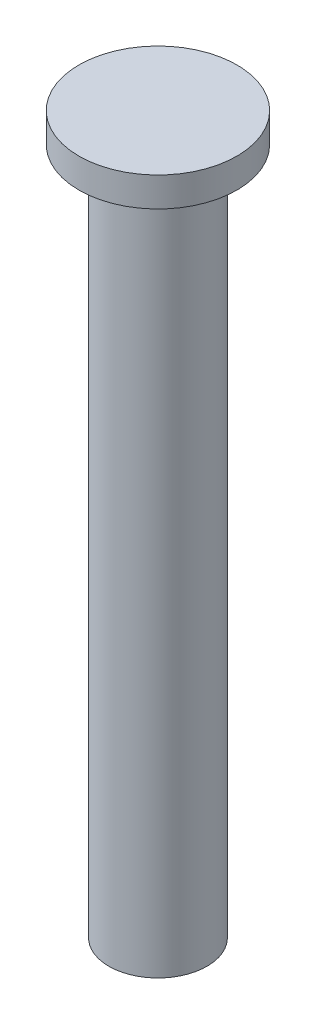
SolidWorks part; units mm, degrees
material "1023 碳钢板 (SS)"
ref_plane "前视基准面" through (0, 0, 0) normal (0, 0, 1) x (1, 0, 0)
ref_plane "上视基准面" through (0, 0, 0) normal (0, 1, 0) x (1, 0, 0)
ref_plane "右视基准面" through (0, 0, 0) normal (1, 0, 0) x (0, 0, -1)
sketch "草图1" plane through (0, 0, 0) normal (0, 1, 0) x (1, 0, 0)
  circle A0 centre (0, 0) radius 2.5
  dimension "D1" = 5
extrude "凸台-拉伸1" add sketch "草图1" along normal blind 35
sketch "草图2" plane through (0, 35, 0) normal (0, 1, 0) x (1, 0, 0)
  circle A0 centre (0, 0) radius 4.0246
extrude "凸台-拉伸2" add sketch "草图2" along normal blind 1.5
